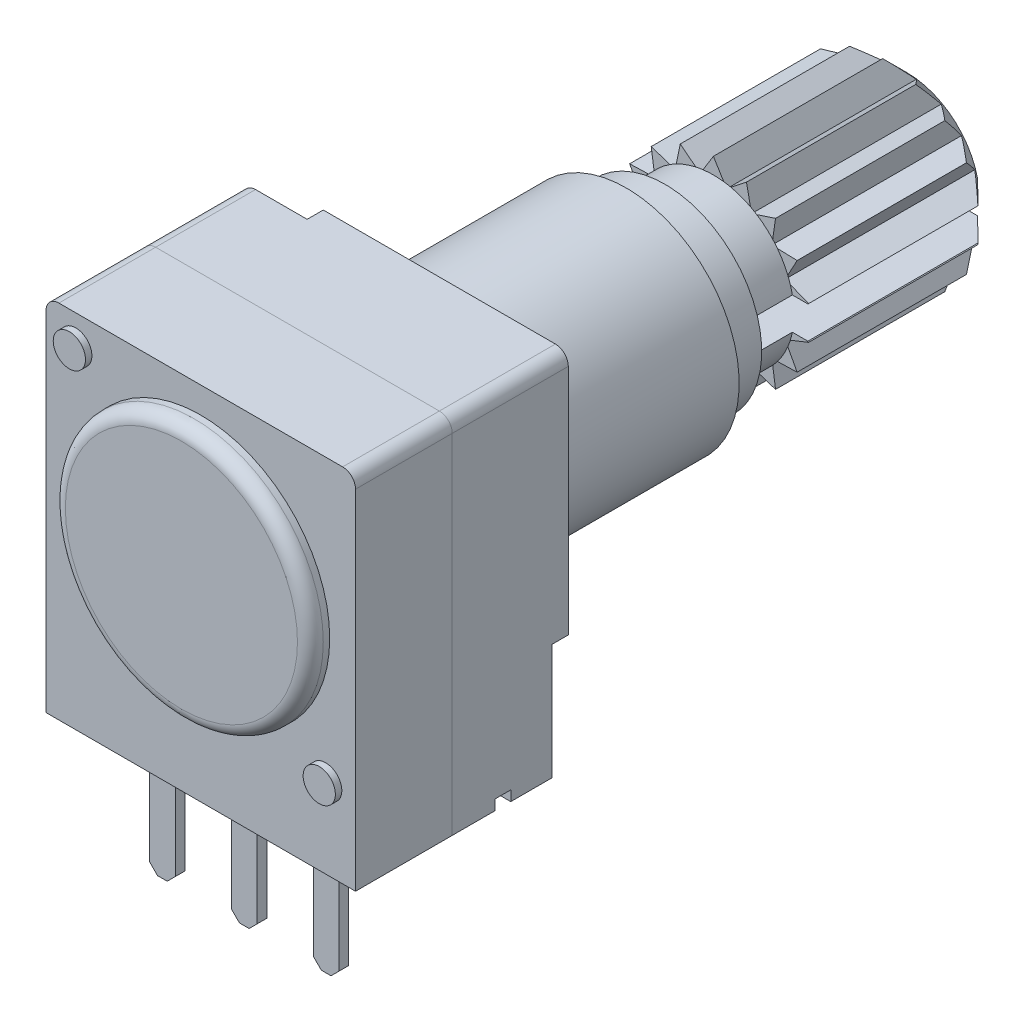
SolidWorks part; units mm, degrees
ref_plane "Front Plane" through (0, 0, 0) normal (0, 0, 1) x (1, 0, 0)
ref_plane "Top Plane" through (0, 0, 0) normal (0, 1, 0) x (1, 0, 0)
ref_plane "Right Plane" through (0, 0, 0) normal (1, 0, 0) x (0, 0, -1)
sketch "Sketch1" plane through (0, 0, 0) normal (0, 0, 1) x (1, 0, 0)
  line L1 (0, 0) -> (9.6, 0)
  line L2 (0, 0) -> (0, 11.2)
  line L3 (0, 11.2) -> (9.6, 11.2)
  line L4 (9.6, 0) -> (9.6, 11.2)
  dimension "D1" = 9.6
  dimension "D2" = 11.2
extrude "Upper Body Extrude" add sketch "Sketch1" along normal blind 3.6
sketch "Sketch13" plane through (0, 0, 3.6) normal (0, 0, 1) x (1, 0, 0)
  line L1 (0, 11.2) -> (9.6, 11.2)
  line L2 (0, 11.2) -> (0, 0)
  line L3 (0, 0) -> (9.6, 0)
  line L4 (9.6, 11.2) -> (9.6, 0)
extrude "Lower Body Extrude" add sketch "Sketch13" along normal blind 3 separate body
sketch "Sketch2" plane through (0, 0, 6.6) normal (0, 0, 1) x (1, 0, 0)
  line L0 (4.8, 11.2) -> (4.8, 0) construction
  line L3 (9.6, 11.2) -> (0, 11.2) construction
  circle A0 centre (4.8, 6.3924) radius 4
  dimension "D1" = 8
extrude "Bottom Dome Extrude" add sketch "Sketch2" along normal blind 0.6
fillet "Dome Fillet" radius 0.4 1 edges at (8.8, 6.3924, 7.2)
sketch "Sketch3" plane through (0, 0, 0) normal (0, 0, -1) x (-1, 0, 0)
  circle A0 centre (-4.8, 6.3924) radius 3.5
extrude "Threaded Section Extrude" add sketch "Sketch3" along normal blind 6.6
sketch "Sketch4" plane through (0, 0, -6.6) normal (0, 0, -1) x (-1, 0, 0)
  circle A0 centre (-4.8, 6.3924) radius 3
  dimension "D1" = 6
extrude "Strain Relief Extrude" add sketch "Sketch4" along normal blind 1.2
sketch "Sketch10" plane through (0, 0, -7.8) normal (0, 0, -1) x (-1, 0, 0)
  circle A0 centre (-4.8, 6.3924) radius 2.5
  dimension "D1" = 5
extrude "Actuator Shaft Extrude" add sketch "Sketch10" along normal blind 1.5
sketch "Sketch11" plane through (0, 0, -9.3) normal (0, 0, -1) x (-1, 0, 0)
  circle A0 centre (-4.8, 6.3924) radius 3
extrude "Slined Section Extrude" add sketch "Sketch11" along normal blind 6
chamfer "Shaft End Chamfer" distance 0.75 angle 45 1 edges at (1.8, 6.3924, -15.3)
sketch "Sketch5" plane through (0, 0, -15.3) normal (0, 0, -1) x (-1, 0, 0)
  line L0 (-4.8, 9.3924) -> (-5.2114, 8.7259)
  line L1 (-4.8, 9.3924) -> (-4.3886, 8.7259)
  line L3 (-4.8, 11.2) -> (-4.8, 0) construction
  line L4 (-3.7739, 9.2115) -> (-3.6153, 8.4444)
  line L5 (-3.7739, 9.2115) -> (-4.3886, 8.7259)
  line L6 (-2.8716, 8.6906) -> (-2.9849, 7.9155)
  line L7 (-2.8716, 8.6906) -> (-3.6153, 8.4444)
  line L8 (-2.2019, 7.8924) -> (-2.5735, 7.2028)
  line L9 (-2.2019, 7.8924) -> (-2.9849, 7.9155)
  line L10 (-1.8456, 6.9134) -> (-2.4306, 6.3924)
  line L11 (-1.8456, 6.9134) -> (-2.5735, 7.2028)
  line L12 (-1.8456, 5.8715) -> (-2.5735, 5.582)
  line L13 (-1.8456, 5.8715) -> (-2.4306, 6.3924)
  line L14 (-2.2019, 4.8924) -> (-2.9849, 4.8694)
  line L15 (-2.2019, 4.8924) -> (-2.5735, 5.582)
  line L16 (-2.8716, 4.0943) -> (-3.6153, 4.3404)
  line L17 (-2.8716, 4.0943) -> (-2.9849, 4.8694)
  line L18 (-3.7739, 3.5733) -> (-4.3886, 4.059)
  line L19 (-3.7739, 3.5733) -> (-3.6153, 4.3404)
  line L20 (-4.8, 3.3924) -> (-5.2114, 4.059)
  line L21 (-4.8, 3.3924) -> (-4.3886, 4.059)
  line L22 (-5.8261, 3.5733) -> (-5.9847, 4.3404)
  line L23 (-5.8261, 3.5733) -> (-5.2114, 4.059)
  line L24 (-6.7284, 4.0943) -> (-6.6151, 4.8694)
  line L25 (-6.7284, 4.0943) -> (-5.9847, 4.3404)
  line L26 (-7.3981, 4.8924) -> (-7.0265, 5.582)
  line L27 (-7.3981, 4.8924) -> (-6.6151, 4.8694)
  line L28 (-7.7544, 5.8715) -> (-7.1694, 6.3924)
  line L29 (-7.7544, 5.8715) -> (-7.0265, 5.582)
  line L30 (-7.7544, 6.9134) -> (-7.0265, 7.2028)
  line L31 (-7.7544, 6.9134) -> (-7.1694, 6.3924)
  line L32 (-7.3981, 7.8924) -> (-6.6151, 7.9155)
  line L33 (-7.3981, 7.8924) -> (-7.0265, 7.2028)
  line L34 (-6.7284, 8.6906) -> (-5.9847, 8.4444)
  line L35 (-6.7284, 8.6906) -> (-6.6151, 7.9155)
  line L36 (-5.8261, 9.2115) -> (-5.2114, 8.7259)
  line L37 (-5.8261, 9.2115) -> (-5.9847, 8.4444)
  circle A0 centre (-4.8, 6.3924) radius 3.245
  circle A1 centre (-4.8, 6.3924) radius 3 construction
  arc A19 (-3.6153, 8.4444) -> (-4.3886, 8.7259) centre (-4.8, 6.3924) ccw [skipped]
  arc A20 (-2.9849, 7.9155) -> (-3.6153, 8.4444) centre (-4.8, 6.3924) ccw [skipped]
  arc A21 (-2.5735, 7.2028) -> (-2.9849, 7.9155) centre (-4.8, 6.3924) ccw [skipped]
  arc A22 (-4.3886, 8.7259) -> (-5.2114, 8.7259) centre (-4.8, 6.3924) ccw [skipped]
  arc A23 (-5.2114, 8.7259) -> (-5.9847, 8.4444) centre (-4.8, 6.3924) ccw [skipped]
  arc A24 (-5.9847, 8.4444) -> (-6.6151, 7.9155) centre (-4.8, 6.3924) ccw [skipped]
  arc A25 (-6.6151, 7.9155) -> (-7.0265, 7.2028) centre (-4.8, 6.3924) ccw [skipped]
  arc A26 (-7.0265, 7.2028) -> (-7.1694, 6.3924) centre (-4.8, 6.3924) ccw [skipped]
  arc A27 (-7.1694, 6.3924) -> (-7.0265, 5.582) centre (-4.8, 6.3924) ccw [skipped]
  arc A28 (-7.0265, 5.582) -> (-6.6151, 4.8694) centre (-4.8, 6.3924) ccw [skipped]
  arc A29 (-6.6151, 4.8694) -> (-5.9847, 4.3404) centre (-4.8, 6.3924) ccw [skipped]
  arc A30 (-5.9847, 4.3404) -> (-5.2114, 4.059) centre (-4.8, 6.3924) ccw [skipped]
  arc A31 (-5.2114, 4.059) -> (-4.3886, 4.059) centre (-4.8, 6.3924) ccw [skipped]
  arc A32 (-4.3886, 4.059) -> (-3.6153, 4.3404) centre (-4.8, 6.3924) ccw [skipped]
  arc A33 (-3.6153, 4.3404) -> (-2.9849, 4.8694) centre (-4.8, 6.3924) ccw [skipped]
  arc A34 (-2.9849, 4.8694) -> (-2.5735, 5.582) centre (-4.8, 6.3924) ccw [skipped]
  arc A35 (-2.5735, 5.582) -> (-2.4306, 6.3924) centre (-4.8, 6.3924) ccw [skipped]
  arc A36 (-2.4306, 6.3924) -> (-2.5735, 7.2028) centre (-4.8, 6.3924) ccw [skipped]
  dimension "D1" = 18
extrude "Spline CUt" cut sketch "Sketch5" against normal blind 6
sketch "Sketch12" plane through (0, 0, -15.3) normal (0, 0, -1) x (-1, 0, 0)
  line L0 (-7.1694, 6.3924) -> (-2.4306, 6.3924) construction
  line L1 (-8.0497, 6.8924) -> (-1.5067, 6.8924)
  line L2 (-8.0497, 6.8924) -> (-8.0497, 5.8924)
  line L3 (-8.0497, 5.8924) -> (-1.5067, 5.8924)
  line L4 (-1.5067, 6.8924) -> (-1.5067, 5.8924)
  dimension "D1" = 1
extrude "Shaft Slot Xut" cut sketch "Sketch12" against normal up to surface (7.5 mm away) up to face at (1.8, 6.3924, -7.8)
sketch "Sketch14" plane through (0, 0, 0) normal (0, -1, 0) x (1, 0, 0)
  line L0 (4.8, 3.6) -> (4.8, 6.6) construction
  line L1 (4.4, 4.95) -> (5.2, 4.95)
  line L2 (4.4, 4.95) -> (4.4, 5.25)
  line L3 (4.4, 5.25) -> (5.2, 5.25)
  line L4 (5.2, 4.95) -> (5.2, 5.25)
  line L5 (0, 3.6) -> (9.6, 3.6) construction
  line L6 (0, 6.6) -> (9.6, 6.6) construction
  line L7 (0, 5.1) -> (4.8, 5.1) construction
  line L8 (0, 6.6) -> (0, 3.6) construction
  line L9 (6.94, 4.95) -> (6.94, 5.25)
  line L10 (7.74, 4.95) -> (7.74, 5.25)
  line L11 (6.94, 5.25) -> (7.74, 5.25)
  line L12 (6.94, 4.95) -> (7.74, 4.95)
  line L13 (1.86, 4.95) -> (1.86, 5.25)
  line L14 (2.66, 4.95) -> (2.66, 5.25)
  line L15 (1.86, 5.25) -> (2.66, 5.25)
  line L16 (1.86, 4.95) -> (2.66, 4.95)
  dimension "D1" = 0.8
  dimension "D2" = 0.3
  dimension "D5" = 2.54
  dimension "D6" = 2.54
  dimension "D3" = 2
  dimension "D4" = 2
extrude "Pin Extrude" add sketch "Sketch14" along normal blind 4
chamfer "Pin Tip FIllet" distance 0.25 angle 45 6 edges at (7.74, -4, 5.1) (6.94, -4, 5.1) (5.2, -4, 5.1) (4.4, -4, 5.1) (2.66, -4, 5.1) (1.86, -4, 5.1)
fillet "Upper Body Edge Fillet" radius 0.4 2 edges at (9.6, 11.2, 1.8) (0, 11.2, 1.8)
fillet "Lower Body Edge Fillet" radius 0.4 2 edges at (0, 11.2, 5.1) (9.6, 11.2, 5.1)
sketch "Sketch15" plane through (0, 0, 0) normal (-1, 0, 0) x (0, 0, 1)
  line L1 (1.7846, -0.1806) -> (2.2812, -0.1806)
  line L2 (1.7846, -0.1806) -> (1.7846, 0.3159)
  line L3 (1.7846, 0.3159) -> (2.2812, 0.3159)
  line L4 (2.2812, -0.1806) -> (2.2812, 0.3159)
extrude "Mounting Face Slot Cut" cut sketch "Sketch15" against normal through all
sketch "Sketch17" plane through (0, 0, 0) normal (0, 0, -1) x (-1, 0, 0)
  line L0 (0, 0) -> (-9.6, 0) construction
  line L1 (-5.8, 0) -> (-3.8, 0)
  line L2 (-5.8, 0) -> (-5.8, 0.6)
  line L3 (-5.8, 0.6) -> (-3.8, 0.6)
  line L4 (-3.8, 0) -> (-3.8, 0.6)
  line L5 (-4.8, 0) -> (-4.8, 5.8924) construction
  line L6 (-2.3505, 5.8924) -> (-7.2495, 5.8924) construction
  dimension "D1" = 2
  dimension "D2" = 0.6
extrude "Locating Pin Extrude" add sketch "Sketch17" along normal blind 1
chamfer "Locating Pin Chamfer" distance 0.1 angle 45 4 edges at (4.8, 0.6, -1) (3.8, 0.3, -1) (4.8, 0, -1) (5.8, 0.3, -1)
sketch "Sketch19" plane through (0, 0, 0) normal (0, 0, -1) x (-1, 0, 0)
  line L0 (0, 10.8) -> (0, 0) construction
  line L1 (-9.6, 11.2) -> (0, 11.2)
  line L2 (-9.6, 11.2) -> (-9.6, 1.6)
  line L3 (-9.6, 1.6) -> (0, 1.6)
  line L4 (0, 11.2) -> (0, 1.6)
  line L5 (-9.2, 11.2) -> (-0.4, 11.2) construction
  circle A0 centre (-4.8, 6.3924) radius 5.5
  dimension "D1" = 9.6
  dimension "D2" = 9.6
sketch "Sketch20" plane through (0, 0, 0) normal (0, 0, -1) x (-1, 0, 0)
  line L0 (-2, 11.2) -> (-2, 9.95)
  line L1 (-9.6, 11.2) -> (0, 11.2) construction
  line L2 (0, 9.2) -> (-1.25, 9.2)
  line L3 (0, 11.2) -> (0, 1.6) construction
  line L4 (-7.6, 1.5848) -> (-7.6, 2.8348)
  line L5 (-9.6, 3.5848) -> (-8.35, 3.5848)
  line L6 (-7.6, 1.5848) -> (-7.6, 0)
  line L7 (-5.8, 0) -> (-9.6, 0) construction
  line L8 (-7.6, 0) -> (-9.6, 0)
  line L9 (-9.6, 0) -> (-9.6, 3.5848)
  line L10 (-2, 11.2) -> (0, 11.2)
  line L11 (0, 11.2) -> (0, 9.2)
  arc A0 (-1.25, 9.2) -> (-2, 9.95) centre (-1.25, 9.95) cw
  arc A1 (-8.35, 3.5848) -> (-7.6, 2.8348) centre (-8.35, 2.8348) cw
  dimension "D1" = 1.25
  dimension "D2" = 1.25
  dimension "D3" = 2
  dimension "D4" = 2
extrude "Body Rivet Recess Cut" cut sketch "Sketch20" against normal blind 0.5
sketch "Sketch18" plane through (0, 0, 0.5) normal (0, 0, -1) x (-1, 0, 0)
  circle A0 centre (-0.9244, 10.2949) radius 0.5
  circle A1 centre (-8.6756, 2.4899) radius 0.5
  circle A2 centre (-4.8, 6.3924) radius 5.5 construction
  dimension "D1" = 1
  dimension "D2" = 2
extrude "Rivet Extrude" add sketch "Sketch18" along normal blind 0.3 and the other way blind 6.3 separate body
sketch "Sketch22" plane through (0, 0, 0) normal (0, -1, 0) x (1, 0, 0)
  line L0 (4.8, 5.25) -> (4.8, 4.95) construction
  line L1 (4.95, 5.25) -> (4.65, 5.25) construction
  line L2 (4.4, 4.95) -> (5.2, 4.95) construction
  line L3 (4.65, 5.1) -> (4.8, 5.1) construction
  line L4 (4.65, 5.25) -> (4.65, 4.95) construction
  circle A0 centre (4.8, 5.1) radius 0.4272
extrude "Alignment Centre-Pin Cut" cut sketch "Sketch22" against normal blind 0.2
equation "\"D2@Sketch18\" = \"D1@Sketch18\""
equation "\"D2@Sketch20\" = \"D1@Sketch20\""
equation "\"D4@Sketch20\" = \"D3@Sketch20\""
